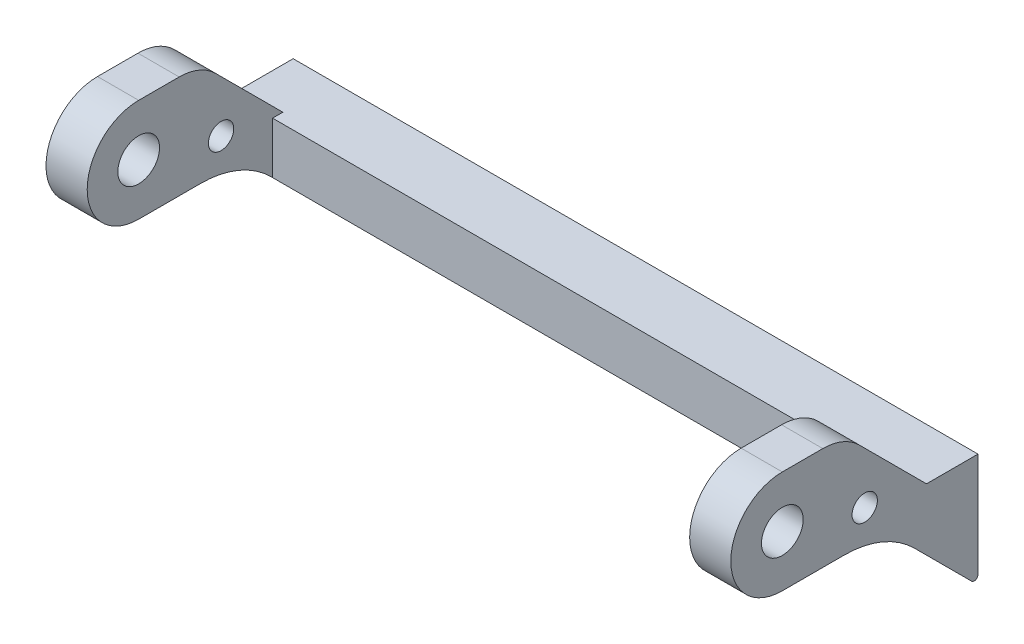
SolidWorks part; units mm, degrees
ref_plane "Front Plane" through (0, 0, 0) normal (1, 0, 0) x (0, 1, 0)
ref_plane "Top Plane" through (0, 0, 0) normal (0, 0, 1) x (0, 1, 0)
ref_plane "Right Plane" through (0, 0, 0) normal (0, 1, 0) x (-1, 0, 0)
sketch "Sketch1" plane through (0, 0, 0) normal (1, 0, 0) x (0, 1, 0)
  line L0 (-11.3854, -10.3854) -> (-5.8284, -4.8284)
  line L1 (-3, 8) -> (-3, 2)
  line L2 (7, 8) -> (7, 4.0711)
  line L3 (5.5355, 0.5355) -> (-1, -6)
  line L7 (-11.1309, -11) -> (-1, -11)
  line L8 (-1, -11) -> (-1, -6)
  circle A0 centre (2, 8) radius 2.025
  circle A1 centre (0, 0) radius 1.2295
  arc A2 (7, 8) -> (-3, 8) centre (2, 8) ccw
  arc A3 (-5.8284, -4.8284) -> (-3, 2) centre (-12.6569, 2) ccw
  arc A4 (-11.3854, -10.3854) -> (-11.1309, -11) centre (-11.1309, -10.64) ccw
  arc A5 (5.5355, 0.5355) -> (7, 4.0711) centre (2, 4.0711) ccw
extrude "Boss-Extrude1" add sketch "Sketch1" along normal blind 4
sketch "Sketch4" plane through (0, 0, 0) normal (-1, 0, 0) x (0, -1, 0)
  line L0 (1, -6) -> (1, -11)
  line L1 (1, -11) -> (11.1309, -11)
  line L3 (5.8284, -4.8284) -> (11.3854, -10.3854) construction
  line L4 (7, -6) -> (11.3854, -10.3854)
  line L5 (1, -6) -> (1, -5)
  line L6 (1, -5) -> (6, -5)
  line L7 (6, -5) -> (7, -6)
  arc A0 (11.1309, -11) -> (11.3854, -10.3854) centre (11.1309, -10.64) ccw
extrude "Boss-Extrude3" add sketch "Sketch4" along normal blind 29.25
ref_plane "Plane2" through (-29.25, 0, 0) normal (1, 0, 0) x (0, 0, -1)
mirror "Mirror8" about plane through (-29.25, 0, 0) normal (1, 0, 0) of "Boss-Extrude3", "Boss-Extrude1"
mirror "Mirror9" about plane through (-29.25, 0, 0) normal (1, 0, 0) of "Boss-Extrude1"
